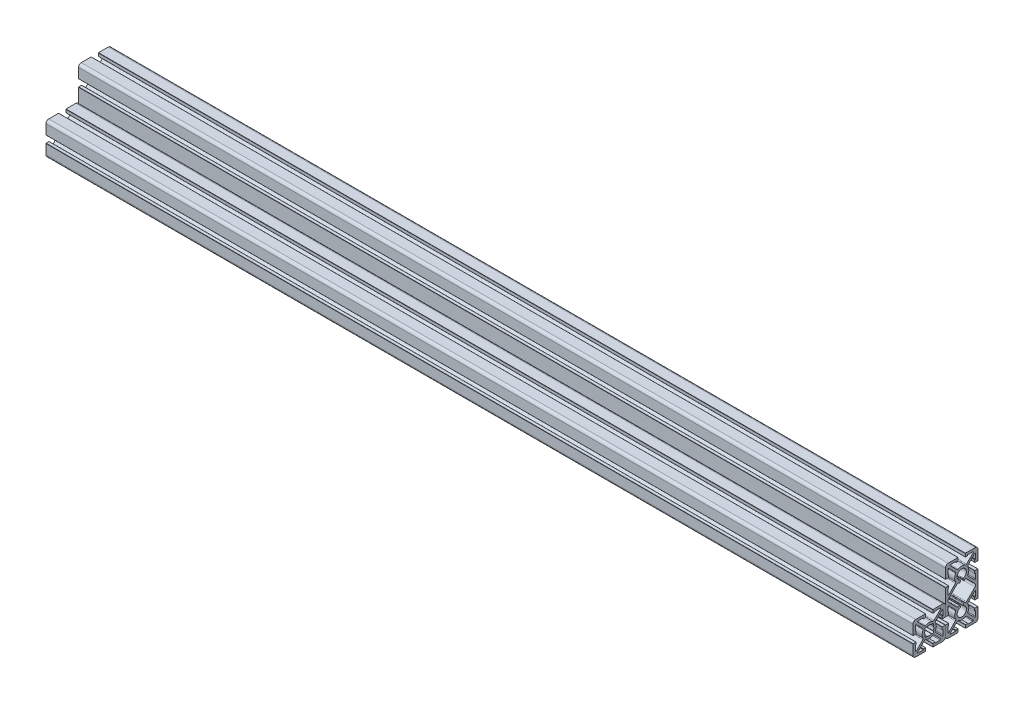
SolidWorks part; units mm, degrees
ref_plane "前视基准面" through (0, 0, 0) normal (0, 0, 1) x (1, 0, 0)
ref_plane "上视基准面" through (0, 0, 0) normal (0, 1, 0) x (1, 0, 0)
ref_plane "右视基准面" through (0, 0, 0) normal (1, 0, 0) x (0, 0, -1)
sketch "草图1" plane through (0, 0, 0) normal (0, 0, 1) x (1, 0, 0)
  line L0 (-87.1056, 0) -> (87.1056, 0) construction
  line L1 (0, 87.1056) -> (0, -87.1056) construction
  line L2 (-400, 0) -> (400, 0)
  dimension "D1" = 800
other "结构构件1"
ref_plane "基准面1" through (-400, 0, 0) normal (1, 0, 0) x (0, 1, 0)
sketch "Sketch11" plane through (-400, 30, -15) normal (1, 0, 0) x (0, 1, 0)
  line L0 (-15, 0) -> (15, 0) construction
  line L1 (11.55, 15) -> (-11.55, 15)
  line L2 (-11.75, 14.8) -> (-11.75, 12.2)
  line L3 (-11.55, 12) -> (-9.55, 12)
  line L4 (-9.55, 12) -> (-9.55, 12.8)
  line L5 (-9.55, 12.8) -> (-4.8213, 12.8)
  line L6 (-4.4678, 11.9464) -> (-10.5958, 5.8184)
  line L7 (-19.4042, 5.8184) -> (-25.5322, 11.9464)
  line L8 (-25.1787, 12.8) -> (-20.45, 12.8)
  line L9 (-20.45, 12.8) -> (-20.45, 12)
  line L10 (-20.45, 12) -> (-18.45, 12)
  line L11 (-18.25, 12.2) -> (-18.25, 14.8)
  line L12 (-18.45, 15) -> (-27.5, 15)
  line L13 (-30, 12.5) -> (-30, 3.45)
  line L14 (-29.8, 3.25) -> (-27.2, 3.25)
  line L15 (-27, 3.45) -> (-27, 5.45)
  line L16 (-27, 5.45) -> (-27.8, 5.45)
  line L17 (-27.8, 5.45) -> (-27.8, 10.1787)
  line L18 (-26.9464, 10.5322) -> (-20.8184, 4.4042)
  line L19 (-20.8184, -4.4042) -> (-26.9464, -10.5322)
  line L20 (-27.8, -10.1787) -> (-27.8, -5.45)
  line L21 (-27.8, -5.45) -> (-27, -5.45)
  line L22 (-27, -5.45) -> (-27, -3.45)
  line L23 (-27.2, -3.25) -> (-29.8, -3.25)
  line L24 (-30, -3.45) -> (-30, -12.5)
  line L25 (-27.5, -15) -> (-18.45, -15)
  line L26 (-18.25, -14.8) -> (-18.25, -12.2)
  line L27 (-18.45, -12) -> (-20.45, -12)
  line L28 (-20.45, -12) -> (-20.45, -12.8)
  line L29 (-20.45, -12.8) -> (-25.1787, -12.8)
  line L30 (-25.5322, -11.9464) -> (-19.4042, -5.8184)
  line L31 (-10.5958, -5.8184) -> (-4.4678, -11.9464)
  line L32 (-4.8213, -12.8) -> (-9.55, -12.8)
  line L33 (-9.55, -12.8) -> (-9.55, -12)
  line L34 (-9.55, -12) -> (-11.55, -12)
  line L35 (-11.75, -12.2) -> (-11.75, -14.8)
  line L36 (-11.55, -15) -> (11.55, -15)
  line L37 (11.75, -14.8) -> (11.75, -12.2)
  line L38 (11.55, -12) -> (9.55, -12)
  line L39 (9.55, -12) -> (9.55, -12.8)
  line L40 (9.55, -12.8) -> (4.8213, -12.8)
  line L41 (4.4678, -11.9464) -> (10.5958, -5.8184)
  line L42 (19.4042, -5.8184) -> (25.5322, -11.9464)
  line L43 (25.1787, -12.8) -> (20.45, -12.8)
  line L44 (20.45, -12.8) -> (20.45, -12)
  line L45 (20.45, -12) -> (18.45, -12)
  line L46 (18.25, -12.2) -> (18.25, -14.8)
  line L47 (18.45, -15) -> (27.5, -15)
  line L48 (30, -12.5) -> (30, -3.45)
  line L49 (29.8, -3.25) -> (27.2, -3.25)
  line L50 (27, -3.45) -> (27, -5.45)
  line L51 (27, -5.45) -> (27.8, -5.45)
  line L52 (27.8, -5.45) -> (27.8, -10.1787)
  line L53 (26.9464, -10.5322) -> (20.8184, -4.4042)
  line L54 (20.8184, 4.4042) -> (26.9464, 10.5322)
  line L55 (27.8, 10.1787) -> (27.8, 5.45)
  line L56 (27.8, 5.45) -> (27, 5.45)
  line L57 (27, 5.45) -> (27, 3.45)
  line L58 (27.2, 3.25) -> (29.8, 3.25)
  line L59 (30, 3.45) -> (30, 12.5)
  line L60 (27.5, 15) -> (18.45, 15)
  line L61 (18.25, 14.8) -> (18.25, 12.2)
  line L62 (18.45, 12) -> (20.45, 12)
  line L63 (20.45, 12) -> (20.45, 12.8)
  line L64 (20.45, 12.8) -> (25.1787, 12.8)
  line L65 (25.5322, 11.9464) -> (19.4042, 5.8184)
  line L66 (10.5958, 5.8184) -> (4.4678, 11.9464)
  line L67 (4.8213, 12.8) -> (9.55, 12.8)
  line L68 (9.55, 12.8) -> (9.55, 12)
  line L69 (9.55, 12) -> (11.55, 12)
  line L70 (11.75, 12.2) -> (11.75, 14.8)
  line L71 (-9.2246, 1.5475) -> (-10.4373, 1.2226)
  line L72 (-10.4373, -1.2226) -> (-9.2246, -1.5475)
  line L73 (-9.1816, -4.4042) -> (-1.4142, -12.1716)
  line L74 (1.4142, -12.1716) -> (9.1816, -4.4042)
  line L75 (9.2246, -1.5475) -> (10.4373, -1.2226)
  line L76 (10.4373, 1.2226) -> (9.2246, 1.5475)
  line L77 (9.1816, 4.4042) -> (1.4142, 12.1716)
  line L78 (-1.4142, 12.1716) -> (-9.1816, 4.4042)
  line L79 (0, 0) -> (0, -18.6858) construction
  arc A0 (-11.55, 15) -> (-11.75, 14.8) centre (-11.55, 14.8) ccw
  arc A1 (-11.75, 12.2) -> (-11.55, 12) centre (-11.55, 12.2) ccw
  arc A2 (-4.4678, 11.9464) -> (-4.8213, 12.8) centre (-4.8213, 12.3) ccw
  arc A3 (-11.7959, 5.6554) -> (-10.5958, 5.8184) centre (-11.303, 6.5255) ccw
  arc A4 (-11.7959, 5.6554) -> (-18.2041, 5.6554) centre (-15, 0) ccw
  arc A5 (-19.4042, 5.8184) -> (-18.2041, 5.6554) centre (-18.697, 6.5255) ccw
  arc A6 (-25.1787, 12.8) -> (-25.5322, 11.9464) centre (-25.1787, 12.3) ccw
  arc A7 (-18.45, 12) -> (-18.25, 12.2) centre (-18.45, 12.2) ccw
  arc A8 (-18.25, 14.8) -> (-18.45, 15) centre (-18.45, 14.8) ccw
  arc A9 (-27.5, 15) -> (-30, 12.5) centre (-27.5, 12.5) ccw
  arc A10 (-30, 3.45) -> (-29.8, 3.25) centre (-29.8, 3.45) ccw
  arc A11 (-27.2, 3.25) -> (-27, 3.45) centre (-27.2, 3.45) ccw
  arc A12 (-26.9464, 10.5322) -> (-27.8, 10.1787) centre (-27.3, 10.1787) ccw
  arc A13 (-20.6554, 3.2041) -> (-20.8184, 4.4042) centre (-21.5255, 3.697) ccw
  arc A14 (-20.6554, 3.2041) -> (-20.6554, -3.2041) centre (-15, 0) ccw
  arc A15 (-20.8184, -4.4042) -> (-20.6554, -3.2041) centre (-21.5255, -3.697) ccw
  arc A16 (-27.8, -10.1787) -> (-26.9464, -10.5322) centre (-27.3, -10.1787) ccw
  arc A17 (-27, -3.45) -> (-27.2, -3.25) centre (-27.2, -3.45) ccw
  arc A18 (-29.8, -3.25) -> (-30, -3.45) centre (-29.8, -3.45) ccw
  arc A19 (-30, -12.5) -> (-27.5, -15) centre (-27.5, -12.5) ccw
  arc A20 (-18.45, -15) -> (-18.25, -14.8) centre (-18.45, -14.8) ccw
  arc A21 (-18.25, -12.2) -> (-18.45, -12) centre (-18.45, -12.2) ccw
  arc A22 (-25.5322, -11.9464) -> (-25.1787, -12.8) centre (-25.1787, -12.3) ccw
  arc A23 (-18.2041, -5.6554) -> (-19.4042, -5.8184) centre (-18.697, -6.5255) ccw
  arc A24 (-18.2041, -5.6554) -> (-11.7959, -5.6554) centre (-15, 0) ccw
  arc A25 (-10.5958, -5.8184) -> (-11.7959, -5.6554) centre (-11.303, -6.5255) ccw
  arc A26 (-4.8213, -12.8) -> (-4.4678, -11.9464) centre (-4.8213, -12.3) ccw
  arc A27 (-11.55, -12) -> (-11.75, -12.2) centre (-11.55, -12.2) ccw
  arc A28 (-11.75, -14.8) -> (-11.55, -15) centre (-11.55, -14.8) ccw
  arc A29 (11.55, -15) -> (11.75, -14.8) centre (11.55, -14.8) ccw
  arc A30 (11.75, -12.2) -> (11.55, -12) centre (11.55, -12.2) ccw
  arc A31 (4.4678, -11.9464) -> (4.8213, -12.8) centre (4.8213, -12.3) ccw
  arc A32 (11.7959, -5.6554) -> (10.5958, -5.8184) centre (11.303, -6.5255) ccw
  arc A33 (11.7959, -5.6554) -> (18.2041, -5.6554) centre (15, 0) ccw
  arc A34 (19.4042, -5.8184) -> (18.2041, -5.6554) centre (18.697, -6.5255) ccw
  arc A35 (25.1787, -12.8) -> (25.5322, -11.9464) centre (25.1787, -12.3) ccw
  arc A36 (18.45, -12) -> (18.25, -12.2) centre (18.45, -12.2) ccw
  arc A37 (18.25, -14.8) -> (18.45, -15) centre (18.45, -14.8) ccw
  arc A38 (27.5, -15) -> (30, -12.5) centre (27.5, -12.5) ccw
  arc A39 (30, -3.45) -> (29.8, -3.25) centre (29.8, -3.45) ccw
  arc A40 (27.2, -3.25) -> (27, -3.45) centre (27.2, -3.45) ccw
  arc A41 (26.9464, -10.5322) -> (27.8, -10.1787) centre (27.3, -10.1787) ccw
  arc A42 (20.6554, -3.2041) -> (20.8184, -4.4042) centre (21.5255, -3.697) ccw
  arc A43 (20.6554, -3.2041) -> (20.6554, 3.2041) centre (15, 0) ccw
  arc A44 (20.8184, 4.4042) -> (20.6554, 3.2041) centre (21.5255, 3.697) ccw
  arc A45 (27.8, 10.1787) -> (26.9464, 10.5322) centre (27.3, 10.1787) ccw
  arc A46 (27, 3.45) -> (27.2, 3.25) centre (27.2, 3.45) ccw
  arc A47 (29.8, 3.25) -> (30, 3.45) centre (29.8, 3.45) ccw
  arc A48 (30, 12.5) -> (27.5, 15) centre (27.5, 12.5) ccw
  arc A49 (18.45, 15) -> (18.25, 14.8) centre (18.45, 14.8) ccw
  arc A50 (18.25, 12.2) -> (18.45, 12) centre (18.45, 12.2) ccw
  arc A51 (25.5322, 11.9464) -> (25.1787, 12.8) centre (25.1787, 12.3) ccw
  arc A52 (18.2041, 5.6554) -> (19.4042, 5.8184) centre (18.697, 6.5255) ccw
  arc A53 (18.2041, 5.6554) -> (11.7959, 5.6554) centre (15, 0) ccw
  arc A54 (10.5958, 5.8184) -> (11.7959, 5.6554) centre (11.303, 6.5255) ccw
  arc A55 (4.8213, 12.8) -> (4.4678, 11.9464) centre (4.8213, 12.3) ccw
  arc A56 (11.55, 12) -> (11.75, 12.2) centre (11.55, 12.2) ccw
  arc A57 (11.75, 14.8) -> (11.55, 15) centre (11.55, 14.8) ccw
  arc A58 (-11.0334, 1.526) -> (-10.4373, 1.2226) centre (-10.5668, 1.7055) ccw
  arc A59 (-11.0334, 1.526) -> (-11.0334, -1.526) centre (-15, 0) ccw
  arc A60 (-10.4373, -1.2226) -> (-11.0334, -1.526) centre (-10.5668, -1.7055) ccw
  arc A61 (-8.8835, -2.1997) -> (-9.2246, -1.5475) centre (-9.354, -2.0305) ccw
  arc A62 (-9.3446, -3.2041) -> (-8.8835, -2.1997) centre (-15, 0) ccw
  arc A63 (-9.3446, -3.2041) -> (-9.1816, -4.4042) centre (-8.4745, -3.697) ccw
  arc A64 (-1.4142, -12.1716) -> (1.4142, -12.1716) centre (0, -10.7574) ccw
  arc A65 (9.1816, -4.4042) -> (9.3446, -3.2041) centre (8.4745, -3.697) ccw
  arc A66 (8.8835, -2.1997) -> (9.3446, -3.2041) centre (15, 0) ccw
  arc A67 (9.2246, -1.5475) -> (8.8835, -2.1997) centre (9.354, -2.0305) ccw
  arc A68 (11.0334, -1.526) -> (10.4373, -1.2226) centre (10.5668, -1.7055) ccw
  arc A69 (11.0334, -1.526) -> (11.0334, 1.526) centre (15, 0) ccw
  arc A70 (10.4373, 1.2226) -> (11.0334, 1.526) centre (10.5668, 1.7055) ccw
  arc A71 (8.8835, 2.1997) -> (9.2246, 1.5475) centre (9.354, 2.0305) ccw
  arc A72 (9.3446, 3.2041) -> (8.8835, 2.1997) centre (15, 0) ccw
  arc A73 (9.3446, 3.2041) -> (9.1816, 4.4042) centre (8.4745, 3.697) ccw
  arc A74 (1.4142, 12.1716) -> (-1.4142, 12.1716) centre (0, 10.7574) ccw
  arc A75 (-9.1816, 4.4042) -> (-9.3446, 3.2041) centre (-8.4745, 3.697) ccw
  arc A76 (-8.8835, 2.1997) -> (-9.3446, 3.2041) centre (-15, 0) ccw
  arc A77 (-9.2246, 1.5475) -> (-8.8835, 2.1997) centre (-9.354, 2.0305) ccw
  point P34 (30, 0)
  point P227 (15, -15)
  point P228 (0, 15)
  point P229 (0, -15)
  point P232 (-30, 0)
  point P233 (-15, -15)
  point P234 (-15, 15)
  point P235 (15, 15)
  point P236 (30, -15)
  point P237 (-30, -15)
  point P238 (-30, 15)
  point P239 (30, 15)
  point P240 (0, 0)
other "结构构件2"
ref_plane "基准面2" through (-400, 0, 0) normal (1, 0, 0) x (0, 1, 0)
sketch "Sketch12" plane through (-400, 15, 15) normal (1, 0, 0) x (0, 1, 0)
  line L10 (0, 0) -> (15, 0) construction
  line L11 (0, 0) -> (0, -15) construction
  line L179 (-14.8, 3.25) -> (-12.2, 3.25)
  line L180 (-12, 3.45) -> (-12, 5.45)
  line L181 (-12, 5.45) -> (-12.8, 5.45)
  line L182 (-12.8, 5.45) -> (-12.8, 10.1787)
  line L183 (-11.9464, 10.5322) -> (-5.8184, 4.4042)
  line L184 (-5.8184, -4.4042) -> (-11.9464, -10.5322)
  line L185 (-12.8, -10.1787) -> (-12.8, -5.45)
  line L186 (-12.8, -5.45) -> (-12, -5.45)
  line L187 (-12, -5.45) -> (-12, -3.45)
  line L188 (-12.2, -3.25) -> (-14.8, -3.25)
  line L189 (-15, -3.45) -> (-15, -12.5)
  line L190 (-12.5, -15) -> (-3.45, -15)
  line L191 (-3.25, -14.8) -> (-3.25, -12.2)
  line L192 (-3.45, -12) -> (-5.45, -12)
  line L193 (-5.45, -12) -> (-5.45, -12.8)
  line L194 (-5.45, -12.8) -> (-10.1787, -12.8)
  line L195 (-10.5322, -11.9464) -> (-4.4042, -5.8184)
  line L196 (4.4042, -5.8184) -> (10.5322, -11.9464)
  line L197 (10.1787, -12.8) -> (5.45, -12.8)
  line L198 (5.45, -12.8) -> (5.45, -12)
  line L199 (5.45, -12) -> (3.45, -12)
  line L200 (3.25, -12.2) -> (3.25, -14.8)
  line L201 (3.45, -15) -> (12.5, -15)
  line L202 (15, -12.5) -> (15, -3.45)
  line L203 (14.8, -3.25) -> (12.2, -3.25)
  line L204 (12, -3.45) -> (12, -5.45)
  line L205 (12, -5.45) -> (12.8, -5.45)
  line L206 (12.8, -5.45) -> (12.8, -10.1787)
  line L207 (11.9464, -10.5322) -> (5.8184, -4.4042)
  line L208 (5.8184, 4.4042) -> (11.9464, 10.5322)
  line L209 (12.8, 10.1787) -> (12.8, 5.45)
  line L210 (12.8, 5.45) -> (12, 5.45)
  line L211 (12, 5.45) -> (12, 3.45)
  line L212 (12.2, 3.25) -> (14.8, 3.25)
  line L213 (15, 3.45) -> (15, 12.5)
  line L214 (12.5, 15) -> (3.45, 15)
  line L215 (3.25, 14.8) -> (3.25, 12.2)
  line L216 (3.45, 12) -> (5.45, 12)
  line L217 (5.45, 12) -> (5.45, 12.8)
  line L218 (5.45, 12.8) -> (10.1787, 12.8)
  line L219 (10.5322, 11.9464) -> (4.4042, 5.8184)
  line L220 (-4.4042, 5.8184) -> (-10.5322, 11.9464)
  line L221 (-10.1787, 12.8) -> (-5.45, 12.8)
  line L222 (-5.45, 12.8) -> (-5.45, 12)
  line L223 (-5.45, 12) -> (-3.45, 12)
  line L224 (-3.25, 12.2) -> (-3.25, 14.8)
  line L225 (-3.45, 15) -> (-12.5, 15)
  line L226 (-15, 12.5) -> (-15, 3.45)
  arc A48 (-3.7705, -2.3615) -> (-3.7363, -2.0254) centre (-4.0001, -2.1684) ccw
  arc A49 (-3.7705, -2.3615) -> (-2.3615, -3.7705) centre (-3.0052, -3.0052) ccw
  arc A50 (-2.0254, -3.7363) -> (-2.3615, -3.7705) centre (-2.1684, -4.0001) ccw
  arc A51 (-2.0254, -3.7363) -> (2.0254, -3.7363) centre (0, 0) ccw
  arc A52 (2.3615, -3.7705) -> (2.0254, -3.7363) centre (2.1684, -4.0001) ccw
  arc A53 (2.3615, -3.7705) -> (3.7705, -2.3615) centre (3.0052, -3.0052) ccw
  arc A54 (3.7363, -2.0254) -> (3.7705, -2.3615) centre (4.0001, -2.1684) ccw
  arc A55 (3.7363, -2.0254) -> (3.7363, 2.0254) centre (0, 0) ccw
  arc A56 (3.7705, 2.3615) -> (3.7363, 2.0254) centre (4.0001, 2.1684) ccw
  arc A57 (3.7705, 2.3615) -> (2.3615, 3.7705) centre (3.0052, 3.0052) ccw
  arc A58 (2.0254, 3.7363) -> (2.3615, 3.7705) centre (2.1684, 4.0001) ccw
  arc A59 (2.0254, 3.7363) -> (-2.0254, 3.7363) centre (0, 0) ccw
  arc A60 (-2.3615, 3.7705) -> (-2.0254, 3.7363) centre (-2.1684, 4.0001) ccw
  arc A61 (-2.3615, 3.7705) -> (-3.7705, 2.3615) centre (-3.0052, 3.0052) ccw
  arc A62 (-3.7363, 2.0254) -> (-3.7705, 2.3615) centre (-4.0001, 2.1684) ccw
  arc A63 (-3.7363, 2.0254) -> (-3.7363, -2.0254) centre (0, 0) ccw
  arc A64 (-15, 3.45) -> (-14.8, 3.25) centre (-14.8, 3.45) ccw
  arc A65 (-12.2, 3.25) -> (-12, 3.45) centre (-12.2, 3.45) ccw
  arc A66 (-11.9464, 10.5322) -> (-12.8, 10.1787) centre (-12.3, 10.1787) ccw
  arc A67 (-5.6554, 3.2041) -> (-5.8184, 4.4042) centre (-6.5255, 3.697) ccw
  arc A68 (-5.6554, 3.2041) -> (-5.6554, -3.2041) centre (0, 0) ccw
  arc A69 (-5.8184, -4.4042) -> (-5.6554, -3.2041) centre (-6.5255, -3.697) ccw
  arc A70 (-12.8, -10.1787) -> (-11.9464, -10.5322) centre (-12.3, -10.1787) ccw
  arc A71 (-12, -3.45) -> (-12.2, -3.25) centre (-12.2, -3.45) ccw
  arc A72 (-14.8, -3.25) -> (-15, -3.45) centre (-14.8, -3.45) ccw
  arc A73 (-15, -12.5) -> (-12.5, -15) centre (-12.5, -12.5) ccw
  arc A74 (-3.45, -15) -> (-3.25, -14.8) centre (-3.45, -14.8) ccw
  arc A75 (-3.25, -12.2) -> (-3.45, -12) centre (-3.45, -12.2) ccw
  arc A76 (-10.5322, -11.9464) -> (-10.1787, -12.8) centre (-10.1787, -12.3) ccw
  arc A77 (-3.2041, -5.6554) -> (-4.4042, -5.8184) centre (-3.697, -6.5255) ccw
  arc A78 (-3.2041, -5.6554) -> (3.2041, -5.6554) centre (0, 0) ccw
  arc A79 (4.4042, -5.8184) -> (3.2041, -5.6554) centre (3.697, -6.5255) ccw
  arc A80 (10.1787, -12.8) -> (10.5322, -11.9464) centre (10.1787, -12.3) ccw
  arc A81 (3.45, -12) -> (3.25, -12.2) centre (3.45, -12.2) ccw
  arc A82 (3.25, -14.8) -> (3.45, -15) centre (3.45, -14.8) ccw
  arc A83 (12.5, -15) -> (15, -12.5) centre (12.5, -12.5) ccw
  arc A84 (15, -3.45) -> (14.8, -3.25) centre (14.8, -3.45) ccw
  arc A85 (12.2, -3.25) -> (12, -3.45) centre (12.2, -3.45) ccw
  arc A86 (11.9464, -10.5322) -> (12.8, -10.1787) centre (12.3, -10.1787) ccw
  arc A87 (5.6554, -3.2041) -> (5.8184, -4.4042) centre (6.5255, -3.697) ccw
  arc A88 (5.6554, -3.2041) -> (5.6554, 3.2041) centre (0, 0) ccw
  arc A89 (5.8184, 4.4042) -> (5.6554, 3.2041) centre (6.5255, 3.697) ccw
  arc A90 (12.8, 10.1787) -> (11.9464, 10.5322) centre (12.3, 10.1787) ccw
  arc A91 (12, 3.45) -> (12.2, 3.25) centre (12.2, 3.45) ccw
  arc A92 (14.8, 3.25) -> (15, 3.45) centre (14.8, 3.45) ccw
  arc A93 (15, 12.5) -> (12.5, 15) centre (12.5, 12.5) ccw
  arc A94 (3.45, 15) -> (3.25, 14.8) centre (3.45, 14.8) ccw
  arc A95 (3.25, 12.2) -> (3.45, 12) centre (3.45, 12.2) ccw
  arc A96 (10.5322, 11.9464) -> (10.1787, 12.8) centre (10.1787, 12.3) ccw
  arc A97 (3.2041, 5.6554) -> (4.4042, 5.8184) centre (3.697, 6.5255) ccw
  arc A98 (3.2041, 5.6554) -> (-3.2041, 5.6554) centre (0, 0) ccw
  arc A99 (-4.4042, 5.8184) -> (-3.2041, 5.6554) centre (-3.697, 6.5255) ccw
  arc A100 (-10.1787, 12.8) -> (-10.5322, 11.9464) centre (-10.1787, 12.3) ccw
  arc A101 (-3.45, 12) -> (-3.25, 12.2) centre (-3.45, 12.2) ccw
  arc A102 (-3.25, 14.8) -> (-3.45, 15) centre (-3.45, 14.8) ccw
  arc A103 (-12.5, 15) -> (-15, 12.5) centre (-12.5, 12.5) ccw
  point P0 (0, 15)
  point P1 (15, 0)
  point P2 (0, -15)
  point P3 (-15, 0)
  point P4 (-15, 15)
  point P5 (-15, -15)
  point P6 (15, -15)
  point P7 (15, 15)
  point P8 (0, 0)
  point P9 (0, 0)
